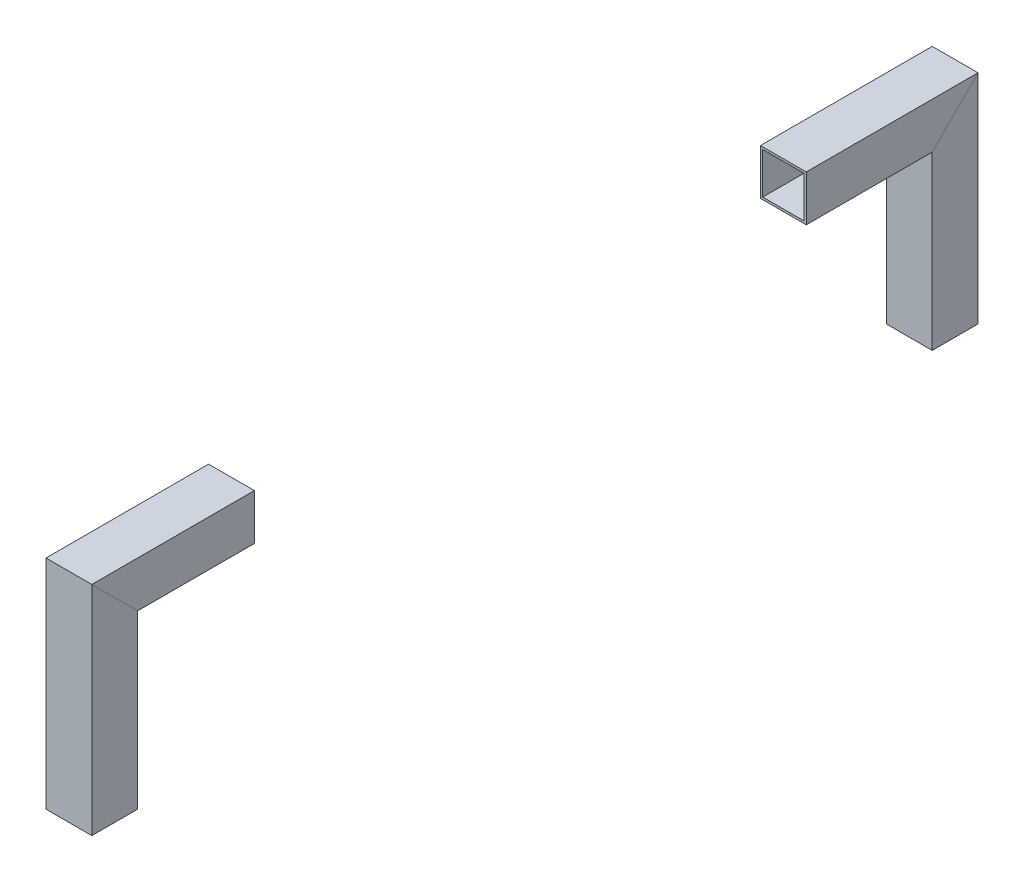
SolidWorks part; units mm, degrees
material "6063-O"
ref_plane "Front" through (0, 0, 0) normal (0, 0, 1) x (1, 0, 0)
ref_plane "Top" through (0, 0, 0) normal (0, 1, 0) x (1, 0, 0)
ref_plane "Right" through (0, 0, 0) normal (1, 0, 0) x (0, 0, -1)
sketch "草图1" plane through (0, 0, 0) normal (1, 0, 0) x (0, 0, -1)
  line L0 (0, 0) -> (0, 85)
  line L1 (0, 85) -> (367, 85)
  line L2 (367, 85) -> (367, 0)
  dimension "D1" = 367
  dimension "D2" = 85
other "铝管 20X20X1(1)"
ref_plane "基准面1" through (0, 0, 0) normal (0, 1, 0) x (0, 0, 1)
sketch "草图11" plane through (0, 0, 0) normal (0, 1, 0) x (0, 0, 1)
  line L1 (-10, -10) -> (10, -10)
  line L2 (-10, -10) -> (-10, 10)
  line L3 (-10, 10) -> (10, 10)
  line L4 (10, -10) -> (10, 10)
  line L5 (-10, -10) -> (10, 10) construction
  line L6 (-10, 10) -> (10, -10) construction
  line L7 (-9, -9) -> (9, -9)
  line L8 (-9, -9) -> (-9, 9)
  line L9 (-9, 9) -> (9, 9)
  line L10 (9, -9) -> (9, 9)
  line L11 (-9, -9) -> (9, 9) construction
  line L12 (-9, 9) -> (9, -9) construction
  point P0 (0, 0)
  point P6 (0, 0)
  point P11 (0, 0)
  dimension "D1" = 20
  dimension "D2" = 20
  dimension "D3" = 18
  dimension "D4" = 18
sketch "草图12" plane through (10, 0, 0) normal (1, 0, 0) x (0, 0, -1)
  line L0 (357, 75) -> (10, 75) construction
  line L1 (-10, 81) -> (314.2891, 81) construction
  line L2 (-10, 95) -> (-10, 0) construction
  line L3 (183.5, 95) -> (183.5, 75) construction
  line L4 (377, 95) -> (-10, 95) construction
  circle A0 centre (133.5, 81) radius 1.5
  circle A1 centre (233.5, 81) radius 1.5
  dimension "D1" = 6
  dimension "D2" = 3
  dimension "D3" = 3
  dimension "D4" = 100
extrude "切除-拉伸1" cut sketch "草图12" against normal up to surface (20 mm away) up to face at (-10, 85, -183.5)
sketch "草图13" plane through (0, 95, 0) normal (0, 1, 0) x (1, 0, 0)
  line L0 (0, 377) -> (0, -10) construction
  line L1 (10, 377) -> (-10, 377) construction
  line L2 (-10, -10) -> (10, -10) construction
  line L3 (-10, 377) -> (10, 377) construction
  line L4 (0, 352) -> (0, -35) construction
  line L5 (0, 327) -> (0, -60) construction
  line L6 (0, 302) -> (0, -85) construction
  line L7 (0, 277) -> (0, -110) construction
  line L8 (0, 252) -> (0, -135) construction
  line L9 (0, 227) -> (0, -160) construction
  line L10 (0, 202) -> (0, -185) construction
  line L11 (0, 177) -> (0, -210) construction
  line L12 (0, 152) -> (0, -235) construction
  line L13 (0, 127) -> (0, -260) construction
  line L14 (0, 102) -> (0, -285) construction
  circle A0 centre (0, 337) radius 6
  circle A1 centre (0, 312) radius 6
  circle A2 centre (0, 287) radius 6
  circle A3 centre (0, 262) radius 6
  circle A4 centre (0, 237) radius 6
  circle A5 centre (0, 212) radius 6
  circle A6 centre (0, 187) radius 6
  circle A7 centre (0, 162) radius 6
  circle A8 centre (0, 137) radius 6
  circle A9 centre (0, 112) radius 6
  circle A10 centre (0, 87) radius 6
  circle A11 centre (0, 62) radius 6
  dimension "D1" = 12
  dimension "D2" = 40
extrude "切除-拉伸2" [suppressed] cut sketch "草图13" against normal through all
sketch "草图14" plane through (10, 0, 0) normal (1, 0, 0) x (0, 0, -1)
  line L0 (357, 75) -> (10, 75) construction
  line L1 (61, 75) -> (302, 75)
  line L2 (61, 75) -> (61, 95)
  line L3 (61, 95) -> (302, 95)
  line L4 (302, 75) -> (302, 95)
  line L5 (377, 95) -> (-10, 95) construction
  line L6 (-10, 95) -> (-10, 0) construction
  line L7 (377, 0) -> (377, 95) construction
  dimension "D1" = 71
  dimension "D2" = 75
extrude "切除-拉伸3" cut sketch "草图14" against normal through all
